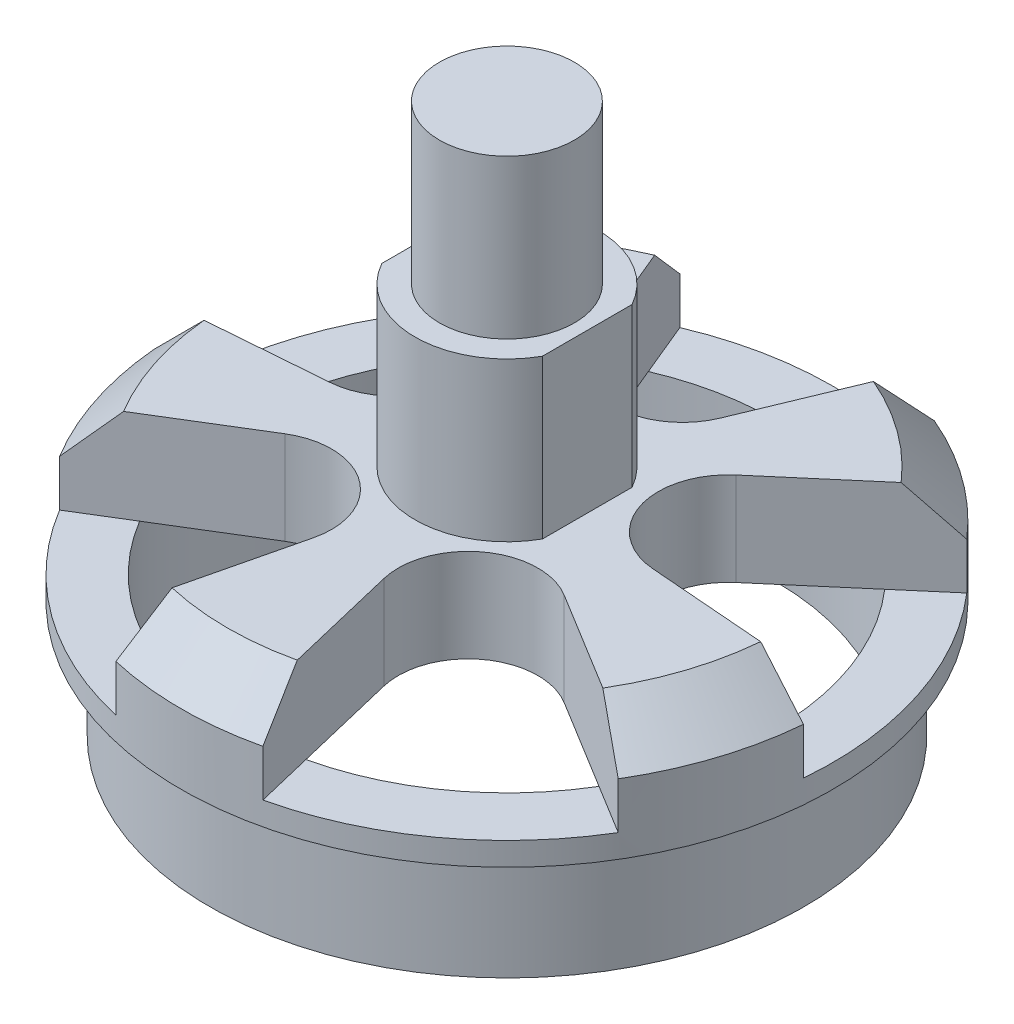
SolidWorks part; units mm, degrees
material "6061 合金"
ref_plane "前视基准面" through (0, 0, 0) normal (0, 0, 1) x (1, 0, 0)
ref_plane "上视基准面" through (0, 0, 0) normal (0, 1, 0) x (1, 0, 0)
ref_plane "右视基准面" through (0, 0, 0) normal (1, 0, 0) x (0, 0, -1)
sketch "草图1" plane through (0, 0, 0) normal (0, 1, 0) x (1, 0, 0)
  circle A0 centre (0, 0) radius 14
  dimension "D1" = 28
extrude "凸台-拉伸1" add sketch "草图1" along normal blind 10
sketch "草图2" plane through (0, 0, 0) normal (0, -1, 0) x (1, 0, 0)
  circle A0 centre (0, 0) radius 11.5
  dimension "D1" = 23
extrude "切除-拉伸1" cut sketch "草图2" against normal blind 6
sketch "草图3" plane through (0, 0, 0) normal (0, -1, 0) x (1, 0, 0)
  circle A0 centre (0, 0) radius 12.75
  circle A1 centre (0, 0) radius 14
  dimension "D1" = 25.5
extrude "切除-拉伸2" cut sketch "草图3" against normal blind 5
sketch "草图4" plane through (0, 10, 0) normal (0, 1, 0) x (1, 0, 0)
  line L0 (-20.0965, 0) -> (19.1891, 0) construction
  line L1 (0, 17.7212) -> (0, 4.5397) construction
  line L2 (-2.7716, 6.3917) -> (-5.4633, 12.89)
  line L3 (2.7716, 6.3917) -> (5.4633, 12.89)
  line L4 (0, 0) -> (0, -18.0948) construction
  line L5 (5.2224, 4.6111) -> (10.5709, 9.1792)
  line L6 (6.9353, -0.6608) -> (13.9474, -1.2127)
  line L7 (5.9992, -3.5418) -> (11.9965, -7.217)
  line L8 (1.5146, -6.8001) -> (3.1566, -13.6395)
  line L9 (-1.5146, -6.8001) -> (-3.1566, -13.6395)
  line L10 (-5.9992, -3.5418) -> (-11.9965, -7.217)
  line L11 (-6.9353, -0.6608) -> (-13.9474, -1.2127)
  line L12 (-5.2224, 4.6111) -> (-10.5709, 9.1792)
  arc A0 (-2.7716, 6.3917) -> (2.7716, 6.3917) centre (0, 7.5397) ccw
  circle A1 centre (0, 0) radius 14 construction
  arc A2 (5.4633, 12.89) -> (-5.4633, 12.89) centre (0, 0) ccw
  arc A3 (-14, 0) -> (14, 0) centre (0, 0) ccw
  arc A4 (5.2224, 4.6111) -> (6.9353, -0.6608) centre (7.1707, 2.3299) ccw
  arc A5 (13.9474, -1.2127) -> (10.5709, 9.1792) centre (0, 0) ccw
  arc A6 (5.9992, -3.5418) -> (1.5146, -6.8001) centre (4.4317, -6.0998) ccw
  arc A7 (3.1566, -13.6395) -> (11.9965, -7.217) centre (0, 0) ccw
  arc A8 (-1.5146, -6.8001) -> (-5.9992, -3.5418) centre (-4.4317, -6.0998) ccw
  arc A9 (-11.9965, -7.217) -> (-3.1566, -13.6395) centre (0, 0) ccw
  arc A10 (-6.9353, -0.6608) -> (-5.2224, 4.6111) centre (-7.1707, 2.3299) ccw
  arc A11 (-10.5709, 9.1792) -> (-13.9474, -1.2127) centre (0, 0) ccw
  point P38 (0, 0)
  circle M1 centre (0, 0) radius 14
  dimension "D1" = 6
  dimension "D2" = 45
  dimension "D3" = 5
extrude "切除-拉伸3" cut sketch "草图4" against normal blind 4 contours L2 A0 L3 M1 | L11 A10 L12 M1 | L9 A8 L10 M1 | L7 A6 L8 M1 | L5 A4 L6 M1
chamfer "倒角1" distance 2 angle 45 5 edges at (0, 10, 14) (13.3148, 10, 4.3262) (8.229, 10, -11.3262) (-8.229, 10, -11.3262) (-13.3148, 10, 4.3262)
sketch "草图5" plane through (0, 10, 0) normal (0, 1, 0) x (1, 0, 0)
  line L0 (-3.45, 1.9235) -> (-3.45, -1.9235)
  line L1 (0, 6.6936) -> (0, -8.1105) construction
  line L2 (3.45, 1.9235) -> (3.45, -1.9235)
  arc A0 (-3.45, -1.9235) -> (3.45, -1.9235) centre (0, 0) ccw
  arc A1 (3.45, 1.9235) -> (-3.45, 1.9235) centre (0, 0) ccw
  dimension "D1" = 7.9
  dimension "D2" = 6.9
extrude "凸台-拉伸2" add sketch "草图5" along normal blind 6.8
sketch "草图6" plane through (0, 16.8, 0) normal (0, 1, 0) x (1, 0, 0)
  circle A0 centre (0, 0) radius 2.9
  dimension "D1" = 5.8
extrude "凸台-拉伸3" add sketch "草图6" along normal blind 6.8
sketch "草图7" plane through (0, 6, 0) normal (0, -1, 0) x (1, 0, 0)
  circle A0 centre (0, 0) radius 1.5
  dimension "D1" = 3
extrude "切除-拉伸4" cut sketch "草图7" against normal blind 5
